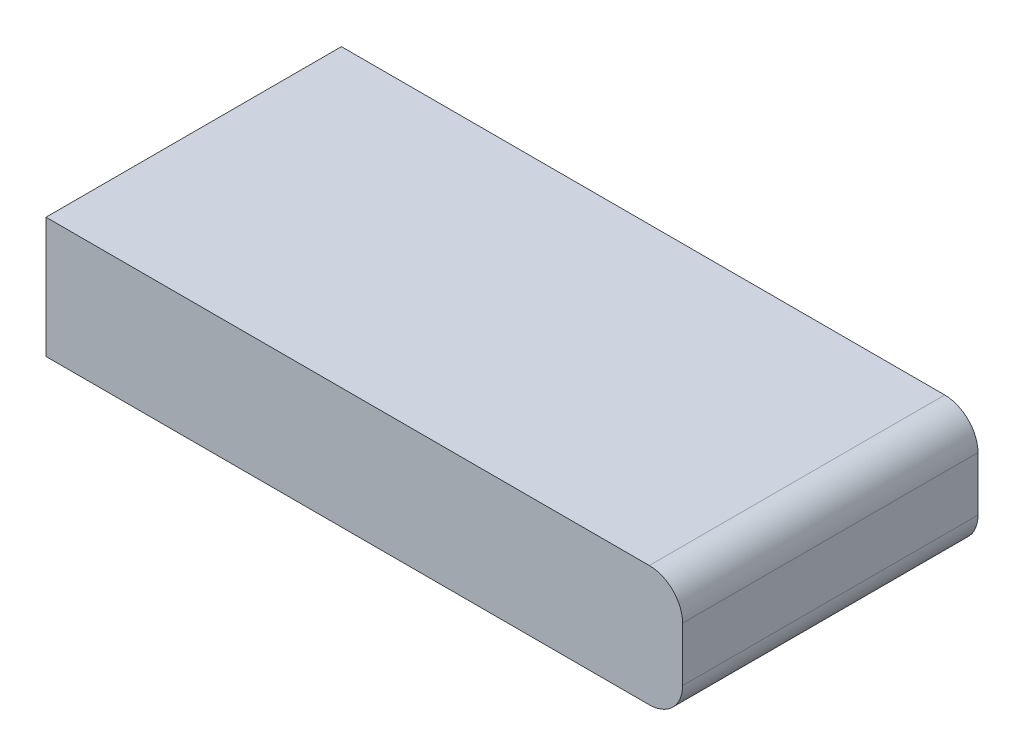
SolidWorks part; units mm, degrees
ref_plane "Front" through (0, 0, 0) normal (0, 0, 1) x (1, 0, 0)
ref_plane "Top" through (0, 0, 0) normal (0, 1, 0) x (1, 0, 0)
ref_plane "Right" through (0, 0, 0) normal (1, 0, 0) x (0, 0, -1)
sketch "草图1" plane through (0, 0, 0) normal (0, 1, 0) x (1, 0, 0)
  line L1 (76.5, -35.5) -> (-76.5, -35.5)
  line L2 (76.5, -35.5) -> (76.5, 35.5)
  line L3 (76.5, 35.5) -> (-76.5, 35.5)
  line L4 (-76.5, -35.5) -> (-76.5, 35.5)
  line L5 (76.5, -35.5) -> (-76.5, 35.5) construction
  line L6 (76.5, 35.5) -> (-76.5, -35.5) construction
  point P0 (0, 0)
extrude "凸台-拉伸1" add sketch "草图1" along normal blind 29
fillet "圆角1" radius 8 1 edges at (76.5, 29, 0)
fillet "圆角2" radius 8 1 edges at (76.5, 0, 0)
